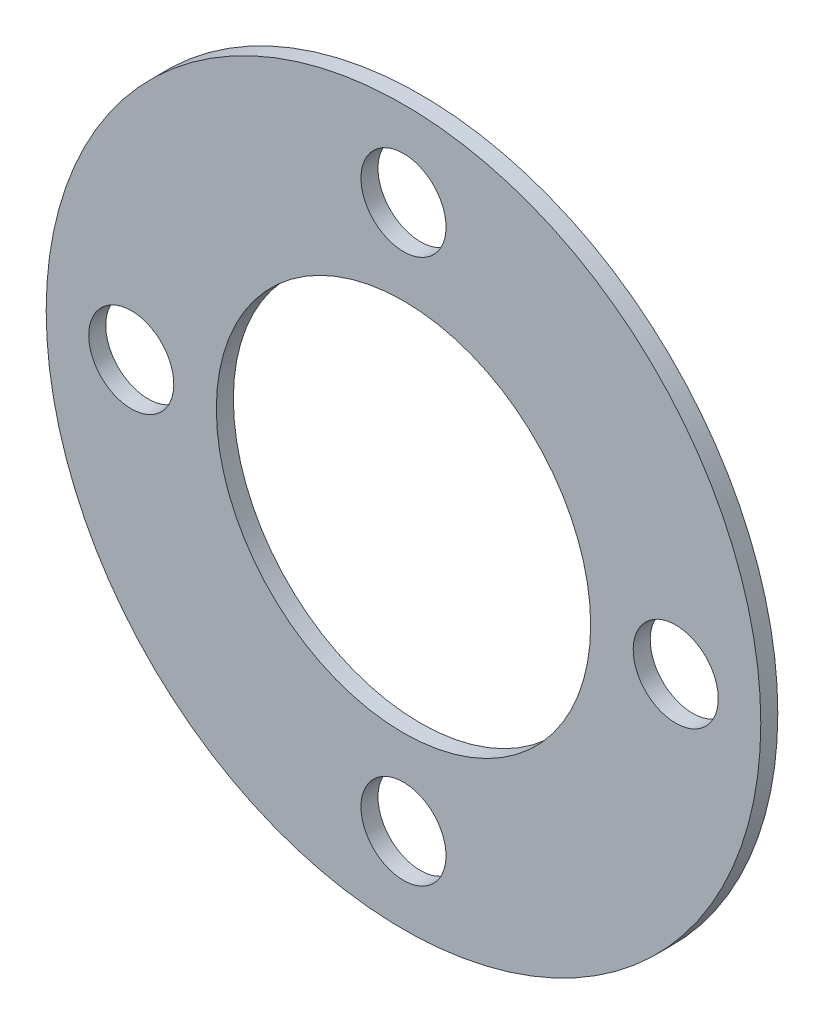
SolidWorks part; units mm, degrees
ref_plane "Спереди" through (0, 0, 0) normal (0, 0, 1) x (1, 0, 0)
ref_plane "Сверху" through (0, 0, 0) normal (0, 1, 0) x (1, 0, 0)
ref_plane "Справа" through (0, 0, 0) normal (1, 0, 0) x (0, 0, -1)
sketch "Эскиз1" plane through (0, 0, 0) normal (0, 0, 1) x (1, 0, 0)
  circle A0 centre (0, 0) radius 21
  circle A1 centre (0, 0) radius 11
  dimension "D1" = 42
  dimension "D2" = 22
extrude "Бобышка-Вытянуть1" add sketch "Эскиз1" along normal blind 1
sketch "Эскиз2" plane through (0, 0, 1) normal (0, 0, 1) x (1, 0, 0)
  line L0 (0, 21) -> (0, 0) construction
  circle A0 centre (0, 0) radius 21 construction
  circle A1 centre (0, 16) radius 2.5
  dimension "D2" = 5
  dimension "D1" = 16
extrude "Вырез-Вытянуть1" cut sketch "Эскиз2" against normal through all
pattern_circular "Круговой массив1" count 4 over 360 about axis through (0, 0, 0) along (0, 0, 1) of "Вырез-Вытянуть1"
